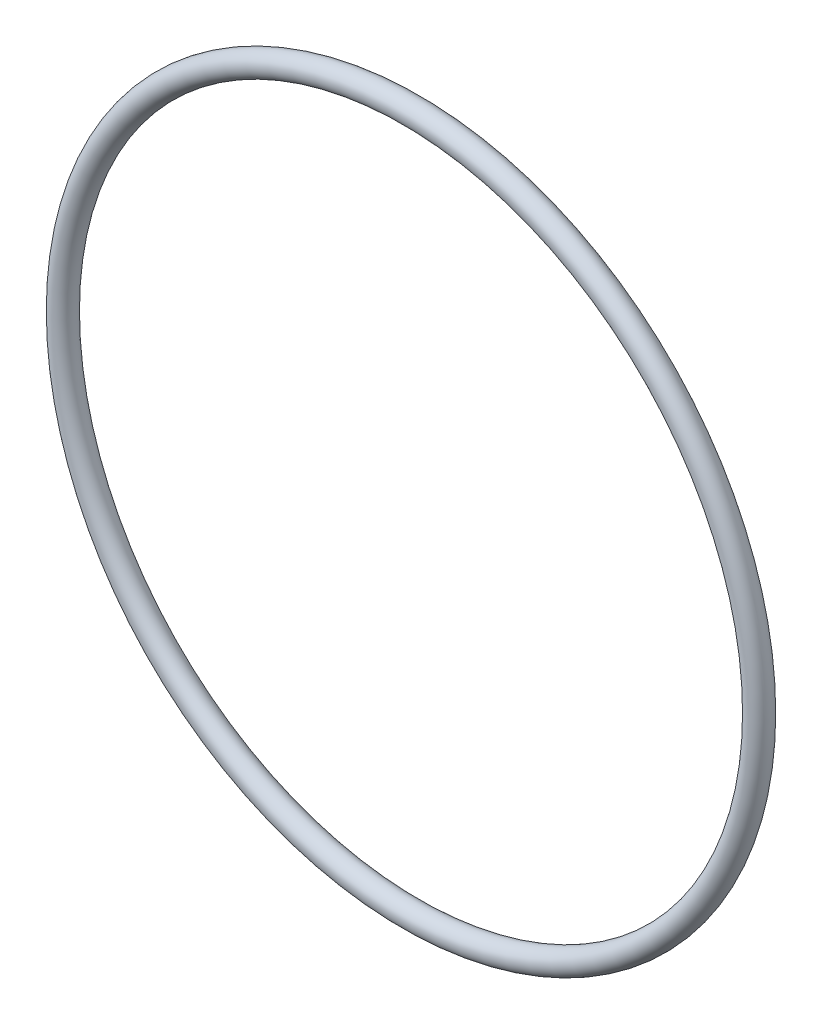
SolidWorks part; units mm, degrees
ref_plane "Front" through (0, 0, 0) normal (0, 0, 1) x (1, 0, 0)
ref_plane "Top" through (0, 0, 0) normal (0, 1, 0) x (1, 0, 0)
ref_plane "Right" through (0, 0, 0) normal (1, 0, 0) x (0, 0, -1)
sketch "Sketch1" plane through (0, 0, 0) normal (1, 0, 0) x (0, -1, 0)
  line L0 (0, -1.7653) -> (0, 1.7653) construction
  line L2 (-57.7939, 0) -> (57.7939, 0) construction
  line L3 (-50.5968, 0) -> (50.5968, 0) construction
  circle A0 centre (52.3621, 0) radius 1.7653
  point P9 (50.5968, 0)
  point P10 (54.1274, 0)
  point P13 (52.3621, 1.7653)
  point P14 (52.3621, -1.7653)
  dimension "Width" = 3.5306
  dimension "ID" = 101.1936
revolve "Revolve1" add sketch "Sketch1" angle 360 about L0
